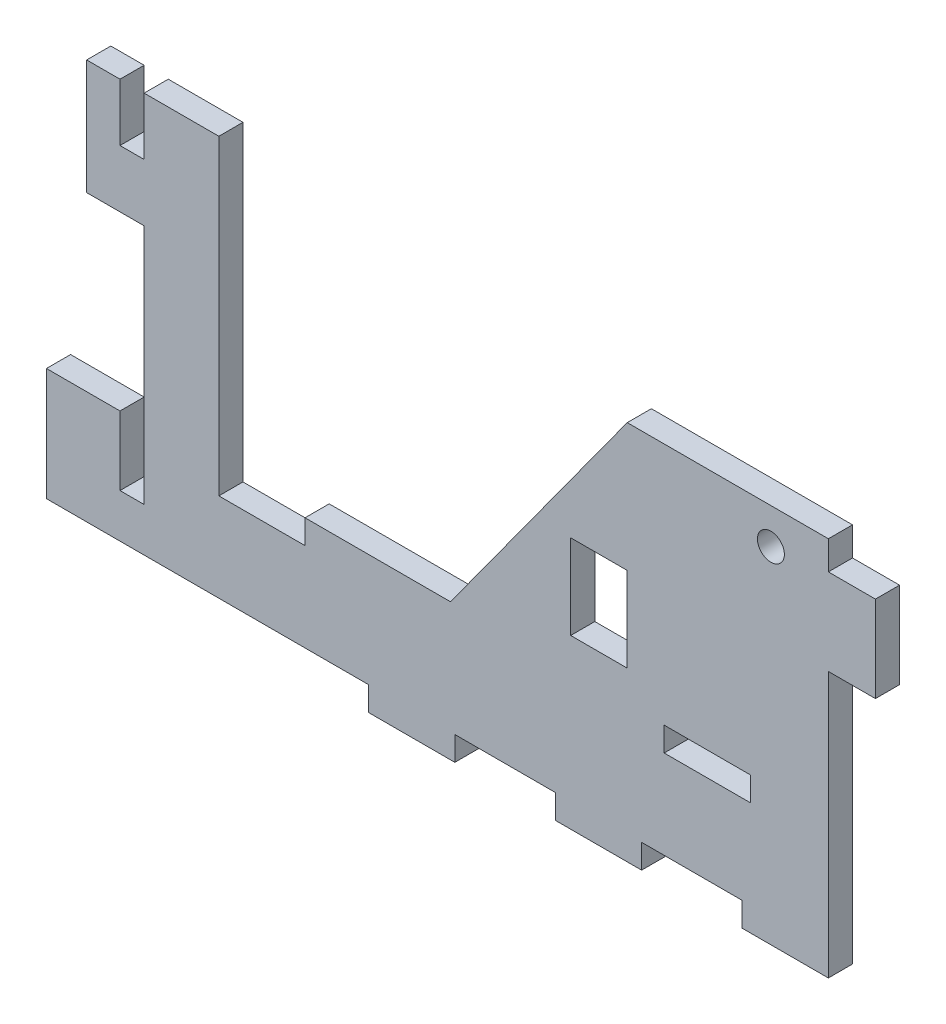
SolidWorks part; units mm, degrees
ref_plane "Front Plane" through (0, 0, 0) normal (0, 0, 1) x (1, 0, 0)
ref_plane "Top Plane" through (0, 0, 0) normal (0, 1, 0) x (1, 0, 0)
ref_plane "Right Plane" through (0, 0, 0) normal (1, 0, 0) x (0, 0, -1)
sketch "Sketch2" plane through (0, 0, 0) normal (0, 0, 1) x (1, 0, 0)
  line L1 (-50.8, 39.37) -> (50.8, 39.37)
  line L2 (-50.8, 39.37) -> (-50.8, -39.37)
  line L3 (-50.8, -39.37) -> (50.8, -39.37)
  line L4 (50.8, 39.37) -> (50.8, -39.37)
  line L5 (-50.8, 39.37) -> (50.8, -39.37) construction
  line L6 (-50.8, -39.37) -> (50.8, 39.37) construction
  point P0 (0, 0)
  dimension "D1" = 78.74
  dimension "D2" = 101.6
extrude "square" add sketch "Sketch2" along normal blind 5.334
sketch "Sketch4" plane through (0, 0, 5.334) normal (0, 0, 1) x (1, 0, 0)
  line L0 (39.2584, 33.5024) -> (25039.2584, 43334.7726) construction
  line L1 (-50.8, -39.37) -> (50.8, -39.37) construction
  line L2 (24.04, 7.1434) -> (24.04, -17.1136) construction
  line L3 (14.515, -14.4466) -> (33.565, -14.4466)
  line L4 (14.515, -14.4466) -> (14.515, -19.7806)
  line L5 (14.515, -19.7806) -> (33.565, -19.7806)
  line L6 (33.565, -14.4466) -> (33.565, -19.7806)
  line L7 (14.515, -14.4466) -> (33.565, -19.7806) construction
  line L8 (14.515, -19.7806) -> (33.565, -14.4466) construction
  line L9 (33.565, -45.7824) -> (50.8, -45.7824) construction
  line L10 (54.6612, -14.4466) -> (54.6612, -39.37) construction
  circle A0 centre (38.1, 31.496) radius 2.975
  circle A1 centre (24.04, 7.1434) radius 3 construction
  point P10 (24.04, -17.1136)
  dimension "D3" = 5.95
  dimension "D6" = 6
  dimension "D1" = 70.866
  dimension "D2" = 12.7
  dimension "D4" = 60
  dimension "D5" = 28.12
  dimension "D7" = 21.59
  dimension "D8" = 19.05
  dimension "D9" = 5.334
  dimension "D10" = 17.235
  dimension "D11" = 24.9234
extrude "Mounting points" cut sketch "Sketch4" against normal through all
sketch "Sketch3" plane through (0, 0, 5.334) normal (0, 0, 1) x (1, 0, 0)
  line L0 (-50.8, -39.37) -> (6.35, 39.37)
  line L1 (50.8, 39.37) -> (-50.8, 39.37) construction
  line L3 (50.8, 39.37) -> (6.35, 39.37)
  dimension "D1" = 44.45
extrude "tricut" cut sketch "Sketch3" against normal through all and the other way through all
sketch "Sketch5" plane through (0, -39.37, 0) normal (0, -1, 0) x (1, 0, 0)
  line L0 (-50.8, 0) -> (50.8, 0) construction
  line L1 (-50.8, 5.334) -> (-31.75, 5.334)
  line L2 (-50.8, 5.334) -> (-50.8, 0)
  line L3 (-50.8, 0) -> (-31.75, 0)
  line L4 (-31.75, 5.334) -> (-31.75, 0)
  line L5 (-50.8, 5.334) -> (50.8, 5.334) construction
  line L6 (-9.525, 5.334) -> (9.525, 5.334)
  line L7 (-9.525, 5.334) -> (-9.525, 0)
  line L8 (-9.525, 0) -> (9.525, 0)
  line L9 (9.525, 5.334) -> (9.525, 0)
  line L11 (50.8, 5.334) -> (31.75, 5.334)
  line L12 (50.8, 5.334) -> (50.8, 0)
  line L13 (50.8, 0) -> (31.75, 0)
  line L14 (31.75, 5.334) -> (31.75, 0)
  dimension "D1" = 19.05
  dimension "D2" = 19.05
  dimension "D3" = 19.05
  dimension "D4" = 22.225
extrude "bottomTeeth" add sketch "Sketch5" along normal blind 5.334
sketch "Sketch8" plane through (50.8, 0, 0) normal (1, 0, 0) x (0, 0, -1)
  line L0 (-5.334, -44.704) -> (-5.334, 39.37) construction
  line L1 (-5.334, 33.02) -> (0, 33.02)
  line L2 (-5.334, 33.02) -> (-5.334, 13.97)
  line L3 (-5.334, 13.97) -> (0, 13.97)
  line L4 (0, 33.02) -> (0, 13.97)
  line L5 (0, -44.704) -> (0, 39.37) construction
  dimension "D1" = 6.35
  dimension "D2" = 19.05
extrude "GrabberStop" add sketch "Sketch8" along normal blind 10.4
sketch "Sketch9" plane through (0, 0, 5.334) normal (0, 0, 1) x (1, 0, 0)
  line L0 (50.8, -44.704) -> (50.8, 13.97) construction
  line L1 (50.8, -39.37) -> (-96.61, -39.37)
  line L2 (50.8, -39.37) -> (50.8, -14.4466)
  line L3 (-96.61, -14.4466) -> (50.8, -14.4466)
  line L4 (-96.61, -39.37) -> (-96.61, -14.4466)
  line L7 (14.515, -14.4466) -> (14.515, -19.7806)
  line L8 (14.515, -19.7806) -> (33.565, -19.7806)
  line L9 (33.565, -14.4466) -> (33.565, -19.7806)
  line L10 (14.515, -14.4466) -> (33.565, -19.7806) construction
  line L11 (14.515, -19.7806) -> (33.565, -14.4466) construction
  point P6 (24.04, -17.1136)
  line M7 (6.35, 39.37) -> (-50.8, -39.37)
  dimension "D1" = 147.41
  dimension "D2" = 24.9234
extrude "UnoPlatform" add sketch "Sketch9" against normal blind 5.334 contours L4 L1 L3 M7
sketch "Sketch13" plane through (0, -14.4466, 0) normal (0, 1, 0) x (1, 0, 0)
  line L0 (-96.61, 0) -> (-32.7105, 0) construction
  line L1 (-83.91, 0) -> (-64.86, 0)
  line L2 (-83.91, 0) -> (-83.91, -5.334)
  line L3 (-83.91, -5.334) -> (-64.86, -5.334)
  line L4 (-64.86, 0) -> (-64.86, -5.334)
  line L5 (-96.61, -5.334) -> (-32.7105, -5.334) construction
  dimension "D1" = 12.7
  dimension "D2" = 19.05
extrude "backTooth" cut sketch "Sketch13" against normal blind 5.334
sketch "Sketch14" plane through (-96.61, 0, 0) normal (-1, 0, 0) x (0, 0, 1)
  line L1 (0, -14.4466) -> (5.334, -14.4466)
  line L2 (0, -14.4466) -> (0, -39.37)
  line L3 (0, -39.37) -> (5.334, -39.37)
  line L4 (5.334, -14.4466) -> (5.334, -39.37)
extrude "CircuitStackExtension" add sketch "Sketch14" along normal blind 25.4
sketch "Sketch16" plane through (0, 0, 5.334) normal (0, 0, 1) x (1, 0, 0)
  line L0 (-122.01, -14.4466) -> (-83.91, -14.4466) construction
  line L1 (-105.754, -14.4466) -> (-100.42, -14.4466)
  line L2 (-105.754, -14.4466) -> (-105.754, -29.6866)
  line L3 (-105.754, -29.6866) -> (-100.42, -29.6866)
  line L4 (-100.42, -14.4466) -> (-100.42, -29.6866)
  dimension "D1" = 16.51
  dimension "D2" = 5.334
  dimension "D3" = 15.24
extrude "CircuitStackHolder" cut sketch "Sketch16" against normal through all
sketch "Sketch17" plane through (0, -14.4466, 0) normal (0, 1, 0) x (1, 0, 0)
  line L1 (-100.42, 0) -> (-83.91, 0)
  line L2 (-100.42, 0) -> (-100.42, -5.334)
  line L3 (-100.42, -5.334) -> (-83.91, -5.334)
  line L4 (-83.91, 0) -> (-83.91, -5.334)
extrude "Braces" add sketch "Sketch17" along normal blind 63.5
sketch "Sketch18" plane through (-100.42, 0, 0) normal (-1, 0, 0) x (0, 0, 1)
  line L0 (0, -29.6866) -> (0, 49.0534) construction
  line L1 (5.334, -29.6866) -> (5.334, 49.0534) construction
  line L2 (0, 36.3534) -> (5.334, 36.3534)
  line L3 (0, 36.3534) -> (0, 23.6534)
  line L4 (0, 23.6534) -> (5.334, 23.6534)
  line L5 (5.334, 36.3534) -> (5.334, 23.6534)
  dimension "D1" = 12.7
  dimension "D2" = 12.7
extrude "Brace2" add sketch "Sketch18" along normal blind 12.7
sketch "Sketch19" plane through (0, 36.3534, 0) normal (0, 1, 0) x (1, 0, 0)
  line L0 (-113.12, -5.334) -> (-100.42, -5.334) construction
  line L1 (-113.12, 0) -> (-105.754, 0)
  line L2 (-113.12, 0) -> (-113.12, -5.334)
  line L3 (-113.12, -5.334) -> (-105.754, -5.334)
  line L4 (-105.754, 0) -> (-105.754, -5.334)
  dimension "D1" = 5.334
extrude "Brace3" add sketch "Sketch19" along normal blind 12.7
sketch "Sketch20" plane through (0, 0, 5.334) normal (0, 0, 1) x (1, 0, 0)
  line L1 (-6.15, 11.08) -> (6.35, 11.08)
  line L2 (-6.15, 11.08) -> (-6.15, -7.62)
  line L3 (-6.15, -7.62) -> (6.35, -7.62)
  line L4 (6.35, 11.08) -> (6.35, -7.62)
  dimension "D1" = 31.75
  dimension "D2" = 44.45
  dimension "D3" = 12.5
  dimension "D4" = 18.7
extrude "On\\Off Switch" cut sketch "Sketch20" against normal through all
